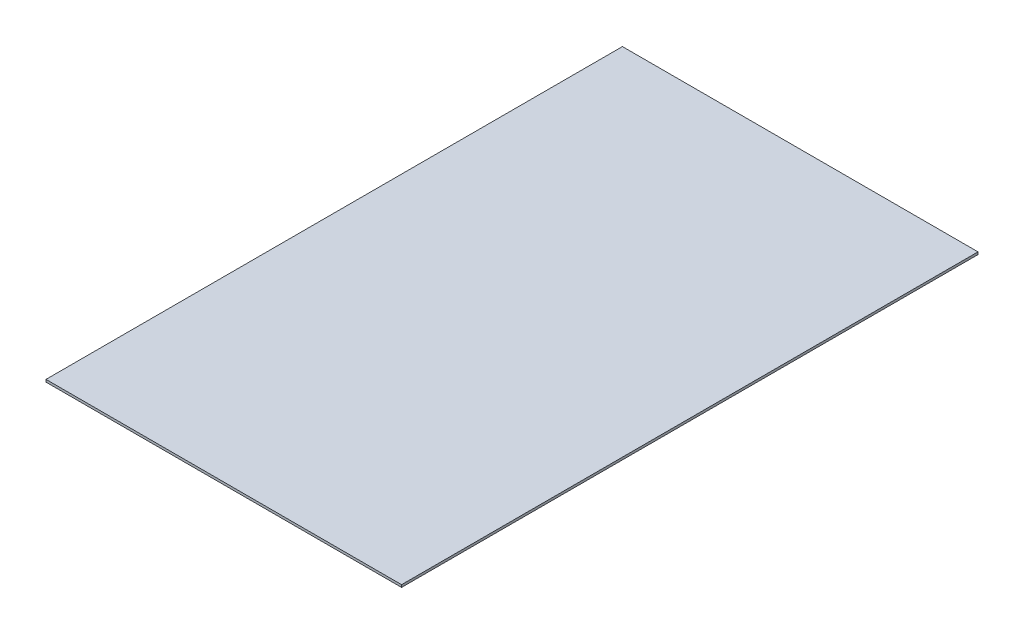
SolidWorks part; units mm, degrees
material "Custom Plastic"
ref_plane "Front Plane" through (0, 0, 0) normal (0, 0, 1) x (1, 0, 0)
ref_plane "Top Plane" through (0, 0, 0) normal (0, 1, 0) x (1, 0, 0)
ref_plane "Right Plane" through (0, 0, 0) normal (1, 0, 0) x (0, 0, -1)
sketch "Sketch1" plane through (0, 0, 0) normal (0, 1, 0) x (1, 0, 0)
  line L1 (-162.6, 263.6) -> (162.6, 263.6)
  line L2 (-162.6, 263.6) -> (-162.6, -263.6)
  line L3 (-162.6, -263.6) -> (162.6, -263.6)
  line L4 (162.6, 263.6) -> (162.6, -263.6)
  line L5 (-162.6, 263.6) -> (162.6, -263.6) construction
  line L6 (-162.6, -263.6) -> (162.6, 263.6) construction
  point P0 (0, 0)
  dimension "D1" = 527.2
  dimension "D2" = 325.2
extrude "Boss-Extrude1" add sketch "Sketch1" along normal blind 2.2
